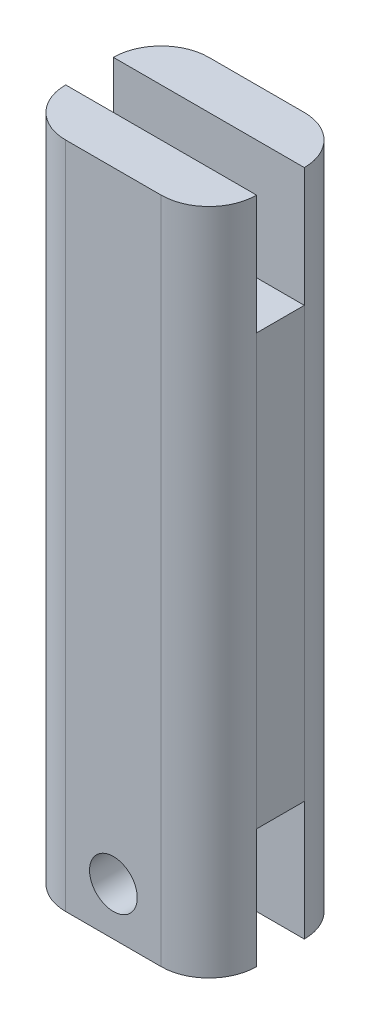
SolidWorks part; units mm, degrees
ref_plane "Front Plane" through (0, 0, 0) normal (0, 0, 1) x (1, 0, 0)
ref_plane "Top Plane" through (0, 0, 0) normal (0, 1, 0) x (1, 0, 0)
ref_plane "Right Plane" through (0, 0, 0) normal (1, 0, 0) x (0, 0, -1)
sketch "Sketch1" plane through (0, 0, 0) normal (0, 1, 0) x (1, 0, 0)
  line L1 (0, 0) -> (10.16, 0)
  line L2 (0, 0) -> (0, 7.62)
  line L3 (0, 7.62) -> (10.16, 7.62)
  line L4 (10.16, 0) -> (10.16, 7.62)
  dimension "D1" = 10.16
  dimension "D2" = 7.62
extrude "Boss-Extrude1" add sketch "Sketch1" along normal blind 35.56
fillet "Fillet1" radius 2.54 4 edges at (0, 17.78, -7.62) (0, 17.78, 0) (10.16, 17.78, -7.62) (10.16, 17.78, 0)
sketch "Sketch2" plane through (0, 0, 0) normal (0, 1, 0) x (1, 0, 0)
  line L1 (10.16, 2.54) -> (0, 2.54)
  line L2 (10.16, 2.54) -> (10.16, 5.08)
  line L3 (10.16, 5.08) -> (0, 5.08)
  line L4 (0, 2.54) -> (0, 5.08)
extrude "Cut-Extrude1" cut sketch "Sketch2" along normal blind 6.35
ref_plane "Plane1" through (0, 17.78, 0) normal (0, 1, 0) x (1, 0, 0)
mirror "Mirror1" about plane through (0, 17.78, 0) normal (0, 1, 0) of "Cut-Extrude1"
sketch "Sketch3" plane through (0, 0, 0) normal (0, 0, 1) x (1, 0, 0)
  line L0 (4.191, 0) -> (-4.191, 0) construction
  line L4 (2.54, 0) -> (7.62, 0) construction
  circle A0 centre (5.08, 2.54) radius 1.27
  point P7 (5.08, 0)
  dimension "D1" = 2.54
  dimension "D2" = 2.54
extrude "Cut-Extrude2" cut sketch "Sketch3" against normal through all both and the other way through all
